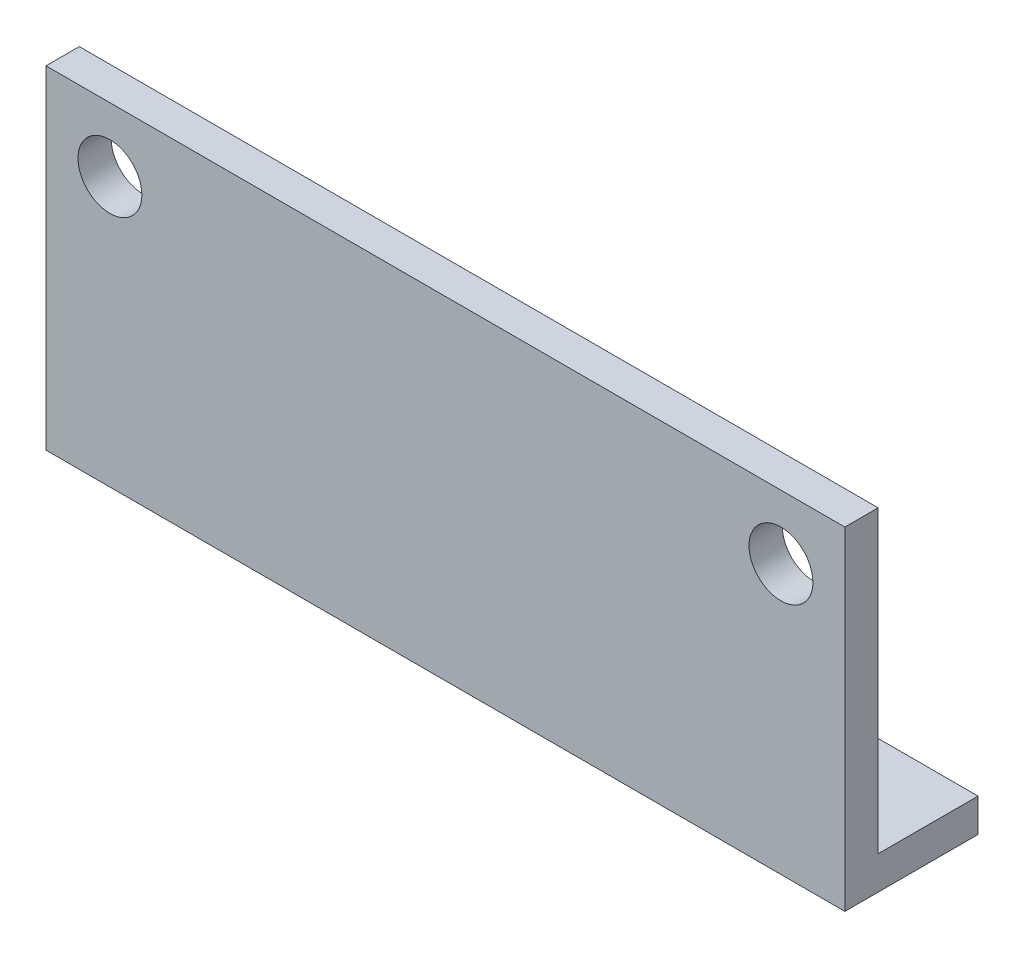
SolidWorks part; units mm, degrees
ref_plane "Front Plane" through (0, 0, 0) normal (0, 0, 1) x (1, 0, 0)
ref_plane "Top Plane" through (0, 0, 0) normal (0, 1, 0) x (1, 0, 0)
ref_plane "Right Plane" through (0, 0, 0) normal (1, 0, 0) x (0, 0, -1)
sketch "Sketch4" plane through (0, 0, 0) normal (1, 0, 0) x (0, 0, -1)
  line L0 (0, 0) -> (0, 0.125)
  line L1 (0, 0.125) -> (0.0125, 0.125)
  line L2 (0.0125, 0.125) -> (0.0125, 0.0125)
  line L3 (0.0125, 0.0125) -> (0.05, 0.0125)
  line L4 (0.05, 0.0125) -> (0.05, 0)
  line L5 (0.05, 0) -> (0, 0)
  dimension "D1" = 0.125
  dimension "D2" = 0.05
  dimension "D3" = 0.0125
extrude "Boss-Extrude2" add sketch "Sketch4" along normal mid plane 0.3
sketch "Sketch6" plane through (0, 0, 0) normal (1, 0, 0) x (0, 0, -1)
  line L0 (0.0125, 0.0125) -> (0.0125, 0.125)
  line L1 (0.0125, 0.125) -> (0.05, 0.0125)
  line L2 (0.05, 0.0125) -> (0.0125, 0.0125)
extrude "Boss-Extrude3" add sketch "Sketch6" along normal mid plane 0.0125
sketch "Sketch7" plane through (0, 0, 0) normal (0, 0, 1) x (1, 0, 0)
  line L0 (-0.15, 0.125) -> (-0.15, 0) construction
  line L1 (0.15, 0.125) -> (-0.15, 0.125) construction
  circle A0 centre (-0.126, 0.101) radius 0.012
  dimension "D1" = 0.024
  dimension "D2" = 0.024
  dimension "D3" = 0.024
extrude "Cut-Extrude2" cut sketch "Sketch7" against normal up to next
mirror "Mirror1" about plane through (0, 0, 0) normal (1, 0, 0) of "Cut-Extrude2"
scale "Scale1" bodies to scale 106 scale about origin uniform scaling yes scale factor 1000
